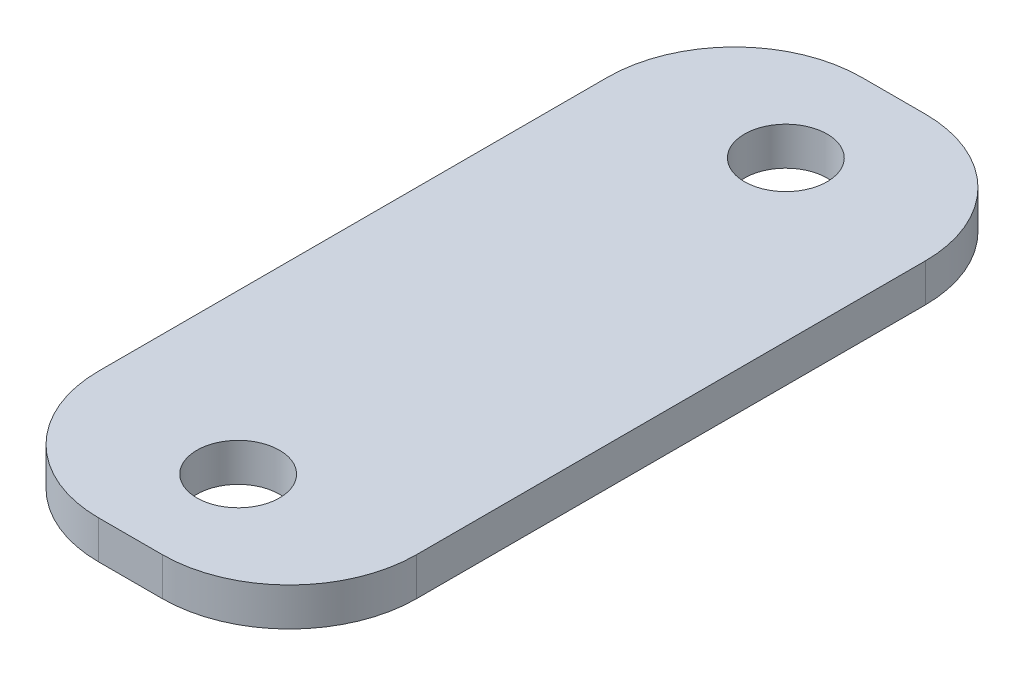
SolidWorks part; units mm, degrees
ref_plane "前视基准面" through (0, 0, 0) normal (0, 0, 1) x (1, 0, 0)
ref_plane "上视基准面" through (0, 0, 0) normal (0, 1, 0) x (1, 0, 0)
ref_plane "右视基准面" through (0, 0, 0) normal (1, 0, 0) x (0, 0, -1)
sketch "草图1" plane through (0, 0, 0) normal (0, 1, 0) x (1, 0, 0)
  line L0 (-12.5, 0) -> (12.5, 0) construction
  line L1 (-12.5, 30) -> (12.5, 30)
  line L2 (-12.5, 30) -> (-12.5, -30)
  line L3 (-12.5, -30) -> (12.5, -30)
  line L4 (12.5, 30) -> (12.5, -30)
  line L5 (-12.5, 30) -> (12.5, -30) construction
  line L6 (-12.5, -30) -> (12.5, 30) construction
  circle A0 centre (0, 21.5306) radius 3.25
  circle A1 centre (0, -21.5306) radius 3.25
  point P0 (0, 0)
  point P12 (0, 21.5306)
  dimension "D3" = 6.5
  dimension "D1" = 25
  dimension "D2" = 60
extrude "凸台-拉伸1" add sketch "草图1" along normal blind 3
fillet "圆角1" radius 10 4 edges at (12.5, 1.5, -30) (-12.5, 1.5, -30) (-12.5, 1.5, 30) (12.5, 1.5, 30)
